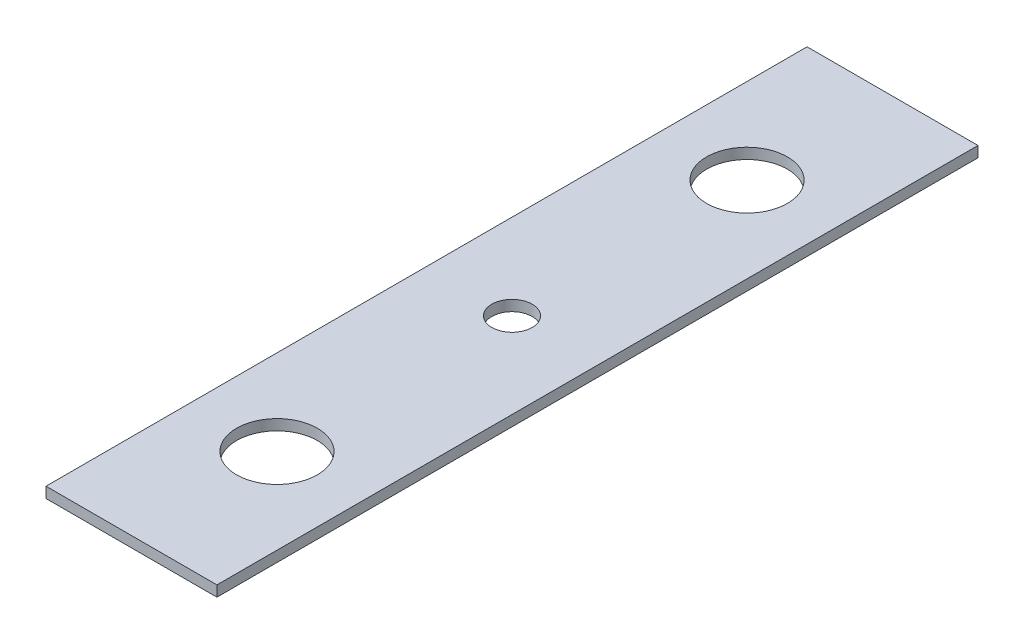
SolidWorks part; units mm, degrees
material "3003-H14"
ref_plane "X-Y Datum" through (0, 0, 0) normal (0, 0, 1) x (1, 0, 0)
ref_plane "X-Z Datum" through (0, 0, 0) normal (0, 1, 0) x (1, 0, 0)
ref_plane "Y-Z Datum" through (0, 0, 0) normal (1, 0, 0) x (0, 0, -1)
sketch "Sketch1" plane through (0, 0, 0) normal (0, 1, 0) x (1, 0, 0)
  line L4 (196.4976, 53.304) -> (196.4976, -3.246)
  line L5 (196.4976, -3.246) -> (209.1976, -3.246)
  line L6 (209.1976, -3.246) -> (209.1976, 53.304)
  line L7 (209.1976, 53.304) -> (196.4976, 53.304)
  line L8 (196.4976, 53.304) -> (196.4976, -3.246)
  line L9 (196.4976, -3.246) -> (209.1976, -3.246)
  line L10 (209.1976, -3.246) -> (209.1976, 53.304)
  line L11 (209.1976, 53.304) -> (196.4976, 53.304)
  circle A0 centre (202.8476, 42.4915) radius 3 construction
  circle A1 centre (202.8476, 7.5665) radius 3 construction
  circle A2 centre (202.8476, 25.029) radius 1.5 construction
  circle A3 centre (202.8476, 7.5665) radius 3
  circle A4 centre (202.8476, 25.029) radius 1.5
  circle A5 centre (202.8476, 42.4915) radius 3
  dimension "D1" = 0
extrude "Boss-Extrude1" add sketch "Sketch1" along normal blind 0.7937
